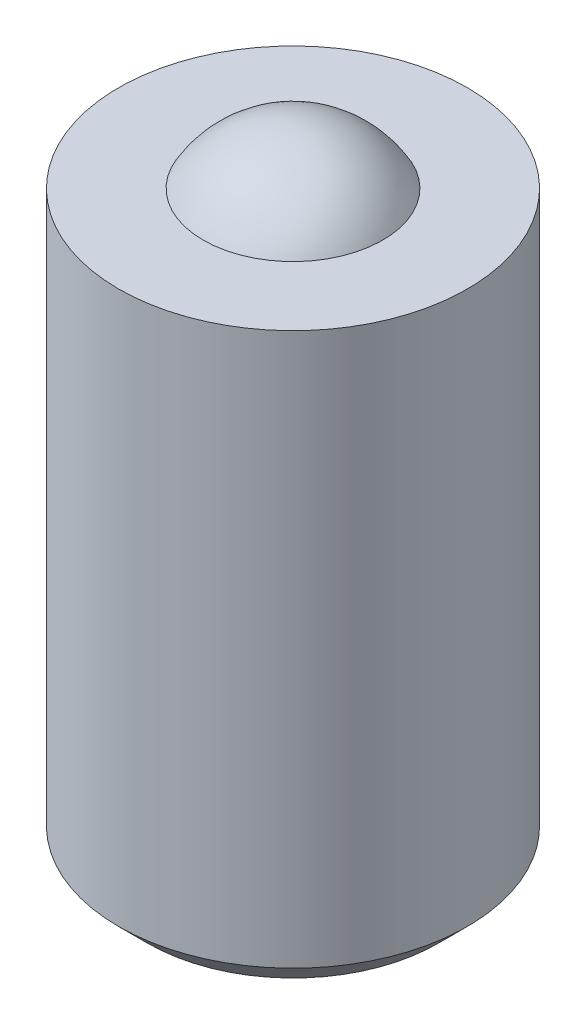
SolidWorks part; units mm, degrees
ref_plane "前视基准面" through (0, 0, 0) normal (0, 0, 1) x (1, 0, 0)
ref_plane "上视基准面" through (0, 0, 0) normal (0, 1, 0) x (1, 0, 0)
ref_plane "右视基准面" through (0, 0, 0) normal (1, 0, 0) x (0, 0, -1)
sketch "草图1" plane through (0, 0, 0) normal (1, 0, 0) x (0, 0, -1)
  line L0 (0, 46.2984) -> (0, -39.6162) construction
  line L1 (-16.4783, 0) -> (19.9104, 0) construction
  line L2 (-3.0887, 0) -> (-6, 0)
  line L3 (-6, 0) -> (-6, -19)
  line L4 (-6, -19) -> (-5, -20)
  line L5 (-5, -20) -> (0, -20)
  line L6 (0, 1.8) -> (0, -20)
  arc A0 (0, 1.8) -> (-3.0887, 0) centre (0, -1.75) ccw
  dimension "D1" = 3.55
  dimension "D4" = 20
  dimension "D2" = 6
  dimension "D3" = 1
  dimension "D5" = 1.75
  dimension "D6" = 1
revolve "旋转1" add sketch "草图1" angle 360 about L0
sketch "草图2" plane through (0, -20, 0) normal (0, -1, 0) x (1, 0, 0)
  line L1 (0, 3.4641) -> (-3, 1.7321)
  line L2 (-3, 1.7321) -> (-3, -1.7321)
  line L3 (-3, -1.7321) -> (0, -3.4641)
  line L4 (0, -3.4641) -> (3, -1.7321)
  line L5 (3, -1.7321) -> (3, 1.7321)
  line L6 (3, 1.7321) -> (0, 3.4641)
  circle A0 centre (0, 0) radius 3 construction
  dimension "D1" = 6
extrude "切除-拉伸1" cut sketch "草图2" against normal blind 3
